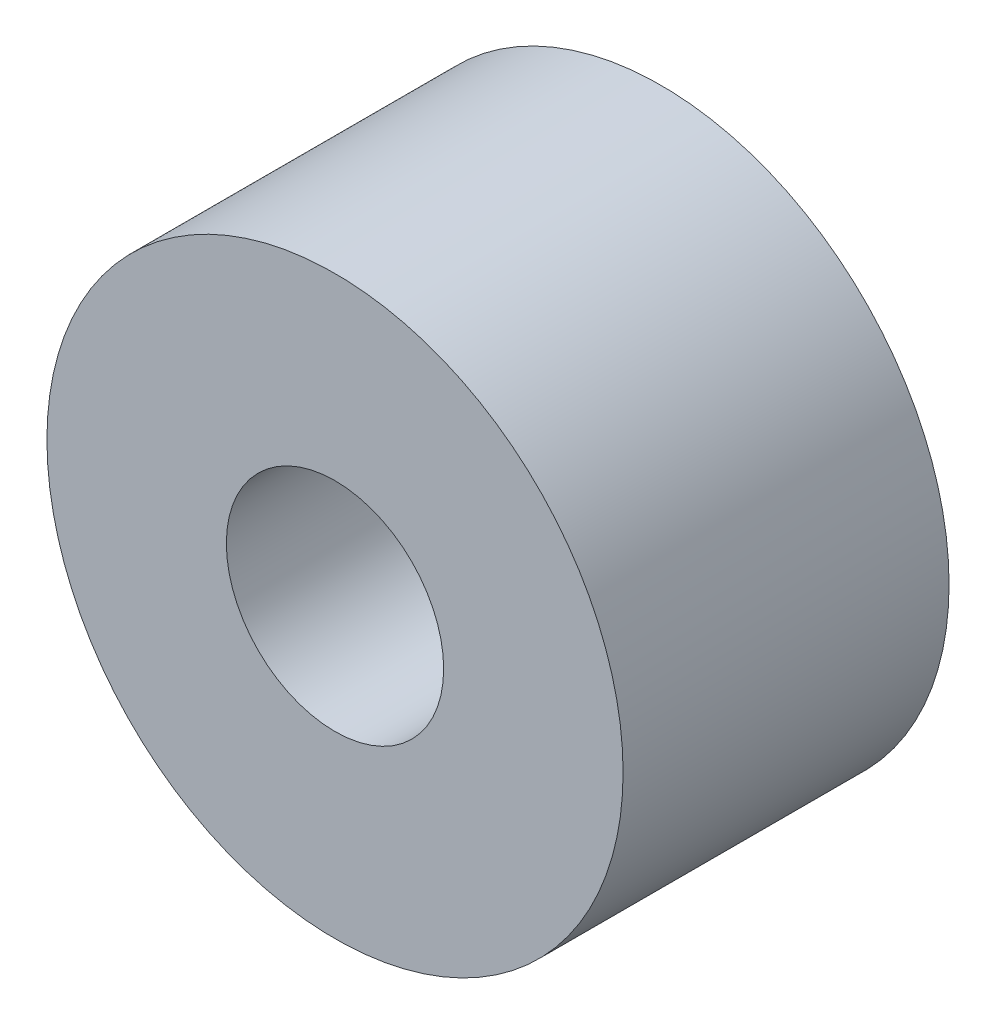
SolidWorks part; units mm, degrees
ref_plane "Front Plane" through (0, 0, 0) normal (0, 0, 1) x (1, 0, 0)
ref_plane "Top Plane" through (0, 0, 0) normal (0, 1, 0) x (1, 0, 0)
ref_plane "Right Plane" through (0, 0, 0) normal (1, 0, 0) x (0, 0, -1)
sketch "Sketch1" plane through (0, 0, 0) normal (0, 0, 1) x (1, 0, 0)
  line L0 (0, 4.6607) -> (0, -4.7212) construction
  line L1 (-5.0132, 0) -> (4.8957, 0) construction
  circle A0 centre (0, 0) radius 4.2088
  circle A1 centre (0, 0) radius 1.5875
extrude "Extrude1" add sketch "Sketch1" along normal mid plane 4.7625
